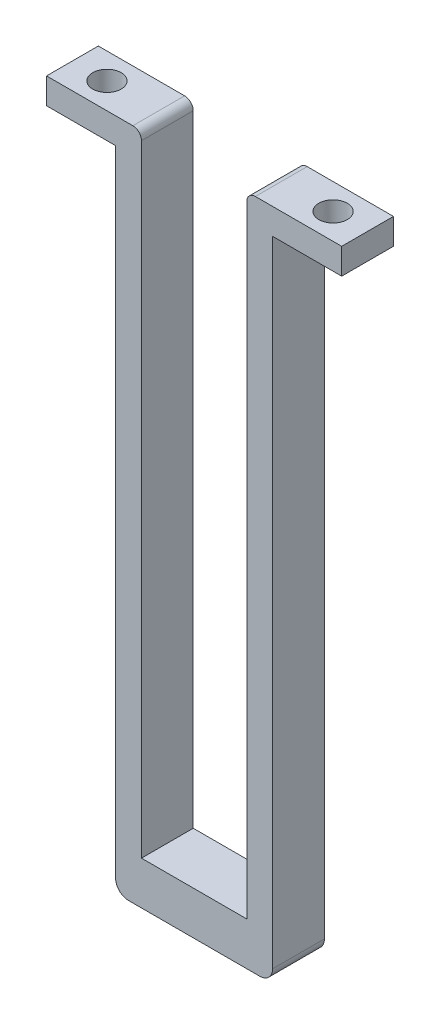
SolidWorks part; units mm, degrees
ref_plane "Front Plane" through (0, 0, 0) normal (0, 0, 1) x (1, 0, 0)
ref_plane "Top Plane" through (0, 0, 0) normal (0, 1, 0) x (1, 0, 0)
ref_plane "Right Plane" through (0, 0, 0) normal (1, 0, 0) x (0, 0, -1)
sketch "Sketch6" plane through (0, 0, 0) normal (0, 0, 1) x (1, 0, 0)
  line L0 (-6.1, 0) -> (6.1, 0)
  line L1 (6.1, 0) -> (6.1, 73)
  line L2 (6.1, 73) -> (17.1, 73)
  line L3 (17.1, 73) -> (17.1, 70)
  line L4 (17.1, 70) -> (9.1, 70)
  line L5 (9.1, 70) -> (9.1, -5)
  line L6 (9.1, -5) -> (-9.1, -5)
  line L7 (0, 4.2064) -> (0, -6.4903) construction
  line L8 (-9.1, 70) -> (-9.1, -5)
  line L9 (-17.1, 70) -> (-9.1, 70)
  line L10 (-17.1, 73) -> (-17.1, 70)
  line L11 (-6.1, 73) -> (-17.1, 73)
  line L12 (-6.1, 0) -> (-6.1, 73)
  point P12 (0, -5)
  point P17 (0, 0)
  dimension "D1" = 6.1
  dimension "D2" = 78
  dimension "D3" = 3
  dimension "D4" = 3
  dimension "D5" = 11
  dimension "D6" = 5
extrude "Boss-Extrude5" add sketch "Sketch6" along normal blind 6
sketch "Sketch7" plane through (0, 70, 0) normal (0, -1, 0) x (1, 0, 0)
  line L0 (-9.1, 6) -> (-9.1, 0) construction
  line L1 (9.1, 6) -> (9.1, 0) construction
  line L2 (-17.1, 6) -> (-9.1, 6) construction
  line L3 (9.1, 6) -> (17.1, 6) construction
  circle A0 centre (-13.1, 3) radius 1.65
  circle A1 centre (13.1, 3) radius 1.65
  dimension "D1" = 3.3
  dimension "D2" = 3.3
  dimension "D3" = 4
  dimension "D4" = 4
  dimension "D5" = 3
  dimension "D6" = 3
extrude "Cut-Extrude2" cut sketch "Sketch7" against normal up to surface (3 mm away) up to face at (-11.6, 73, 3)
fillet "Fillet1" radius 1 2 edges at (-6.1, 73, 3) (6.1, 73, 3)
fillet "Fillet2" radius 1.5 2 edges at (9.1, -5, 3) (-9.1, -5, 3)
equation "\"D2@Sketch7\"=\"D1@Sketch7\""
equation "\"D4@Sketch7\"=\"D3@Sketch7\""
